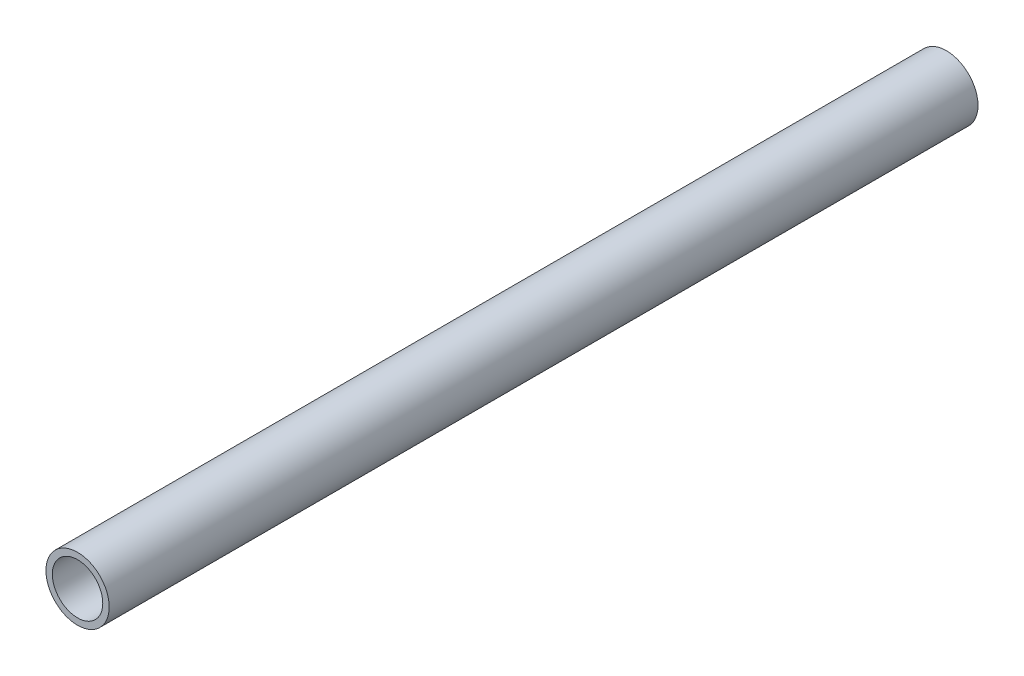
SolidWorks part; units mm, degrees
ref_plane "Front" through (0, 0, 0) normal (0, 0, 1) x (1, 0, 0)
ref_plane "Top" through (0, 0, 0) normal (0, 1, 0) x (1, 0, 0)
ref_plane "Right" through (0, 0, 0) normal (1, 0, 0) x (0, 0, -1)
sketch "Sketch1" plane through (0, 0, 0) normal (0, 0, 1) x (1, 0, 0)
  circle A0 centre (0, 0) radius 16.7005
  circle A1 centre (0, 0) radius 13.3223
  dimension "D1" = 33.401
  dimension "D2" = 26.6446
extrude "Boss-Extrude1" add sketch "Sketch1" along normal mid plane 459
